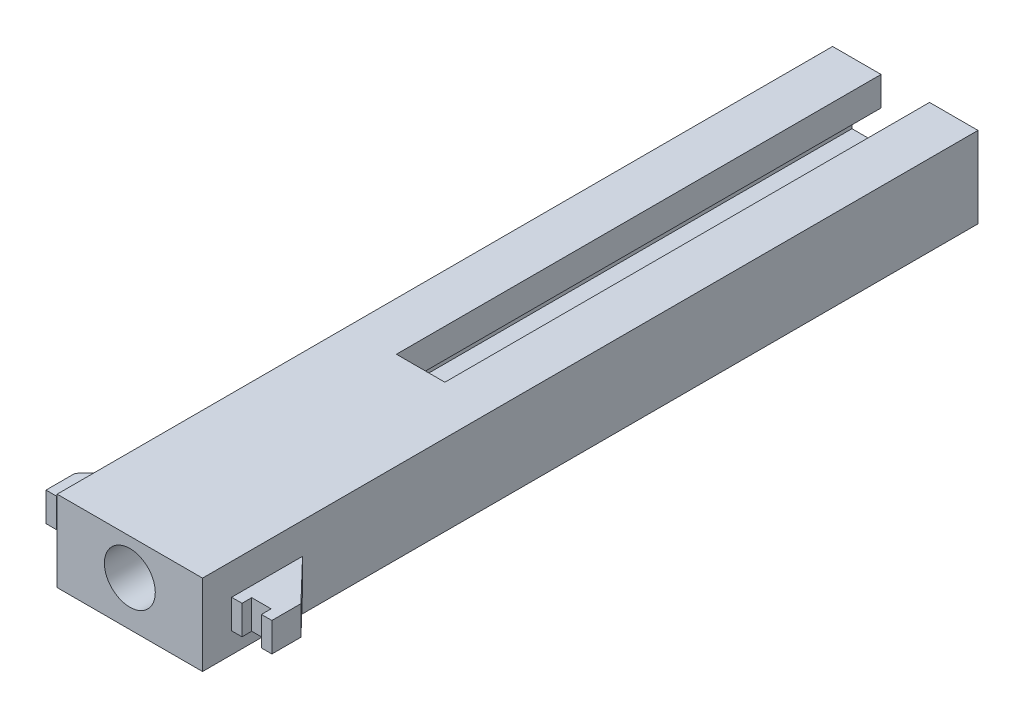
SolidWorks part; units mm, degrees
ref_plane "Front Plane" through (0, 0, 0) normal (0, 0, 1) x (1, 0, 0)
ref_plane "Top Plane" through (0, 0, 0) normal (0, 1, 0) x (1, 0, 0)
ref_plane "Right Plane" through (0, 0, 0) normal (1, 0, 0) x (0, 0, -1)
sketch "Sketch9" plane through (0, 0, 0) normal (0, 0, 1) x (1, 0, 0)
  line L1 (-7.5, 8.35) -> (7.5, 8.35)
  line L2 (-7.5, 8.35) -> (-7.5, 0)
  line L3 (-7.5, 0) -> (7.5, 0)
  line L4 (7.5, 8.35) -> (7.5, 0)
  line L5 (-7.5, 8.35) -> (7.5, 0) construction
  line L6 (-7.5, 0) -> (7.5, 8.35) construction
  point P0 (0, 4.175)
  point P19 (0, 0)
  dimension "D1" = 8.35
  dimension "D2" = 15
extrude "Boss-Extrude4" add sketch "Sketch9" along normal blind 80
sketch "Sketch7" plane through (0, 0, 0) normal (0, 0, 1) x (1, 0, 0)
  line L0 (-5.5, 2) -> (-5.5, 5.35)
  line L1 (-5.5, 5.35) -> (-2.5, 5.35)
  line L2 (-2.5, 5.35) -> (-2.5, 8.35)
  line L3 (-2.5, 8.35) -> (2.5, 8.35) construction
  line L4 (2.5, 8.35) -> (2.5, 5.35)
  line L5 (2.5, 5.35) -> (5.5, 5.35)
  line L6 (5.5, 5.35) -> (5.5, 2)
  line L7 (5.5, 2) -> (-5.5, 2)
  line L9 (7.5, 8.35) -> (-7.5, 8.35) construction
  line L11 (7.5, 0) -> (7.5, 8.35) construction
  line L13 (-2.5, 8.35) -> (2.5, 8.35)
  dimension "D1" = 3.35
  dimension "D2" = 2
  dimension "D3" = 11
  dimension "D4" = 5
  dimension "D5" = 2
extrude "Cut-Extrude4" cut sketch "Sketch7" along normal blind 50
sketch "Sketch10" plane through (0, 0, 80) normal (0, 0, 1) x (1, 0, 0)
  line L0 (5.5, 2) -> (-5.5, 2) construction
  circle A0 centre (0, 4.625) radius 2.625
  dimension "D1" = 5.25
extrude "Cut-Extrude5" cut sketch "Sketch10" against normal up to surface (30 mm away) up to face at (0, 5.2625, 50)
sketch "Sketch12" plane through (7.5, 0, 0) normal (1, 0, 0) x (0, 0, -1)
  line L0 (-80, 0) -> (0, 0) construction
  line L1 (-77, 5.14) -> (-74, 5.14)
  line L2 (-77, 5.14) -> (-77, 2.14)
  line L3 (-77, 2.14) -> (-74, 2.14)
  line L4 (-74, 5.14) -> (-74, 2.14)
  line L5 (-77, 5.14) -> (-74, 2.14) construction
  line L6 (-77, 2.14) -> (-74, 5.14) construction
  line L7 (-80, 0) -> (-80, 8.35) construction
  point P0 (-75.5, 3.64)
  dimension "D1" = 3
  dimension "D2" = 3
  dimension "D3" = 2.14
  dimension "D4" = 3
extrude "Boss-Extrude5" add sketch "Sketch12" along normal blind 4.15
ref_plane "Plane1" through (0, 0, 0) normal (1, 0, 0) x (0, 0, -1)
sketch "Sketch13" plane through (0, 0, 77) normal (0, 0, 1) x (1, 0, 0)
  line L1 (8.575, 5.14) -> (10.575, 5.14)
  line L2 (8.575, 5.14) -> (8.575, 2.14)
  line L3 (8.575, 2.14) -> (10.575, 2.14)
  line L4 (10.575, 5.14) -> (10.575, 2.14)
  line L6 (11.65, 5.14) -> (7.5, 5.14) construction
  line L7 (11.65, 2.14) -> (7.5, 2.14) construction
  point P8 (9.575, 5.14)
  point P9 (9.575, 5.14)
  dimension "D2" = 2
extrude "Cut-Extrude6" cut sketch "Sketch13" against normal blind 1
mirror "Mirror2" about plane through (0, 0, 0) normal (1, 0, 0) of "Boss-Extrude5"
mirror "Mirror4" about plane through (0, 0, 0) normal (1, 0, 0) of "Cut-Extrude6"
sketch "Sketch14" plane through (0, 5.14, 0) normal (0, 1, 0) x (1, 0, 0)
  line L0 (11.65, -74) -> (7.5, -69.6855)
  line L1 (7.5, -80) -> (7.5, 0) construction
  line L2 (7.5, -69.6855) -> (7.5, -74)
  line L3 (7.5, -74) -> (11.65, -74)
extrude "Boss-Extrude6" add sketch "Sketch14" against normal up to surface (3 mm away) up to face at (9.575, 2.14, 76)
mirror "Mirror5" about plane through (0, 0, 0) normal (1, 0, 0) of "Boss-Extrude6"
